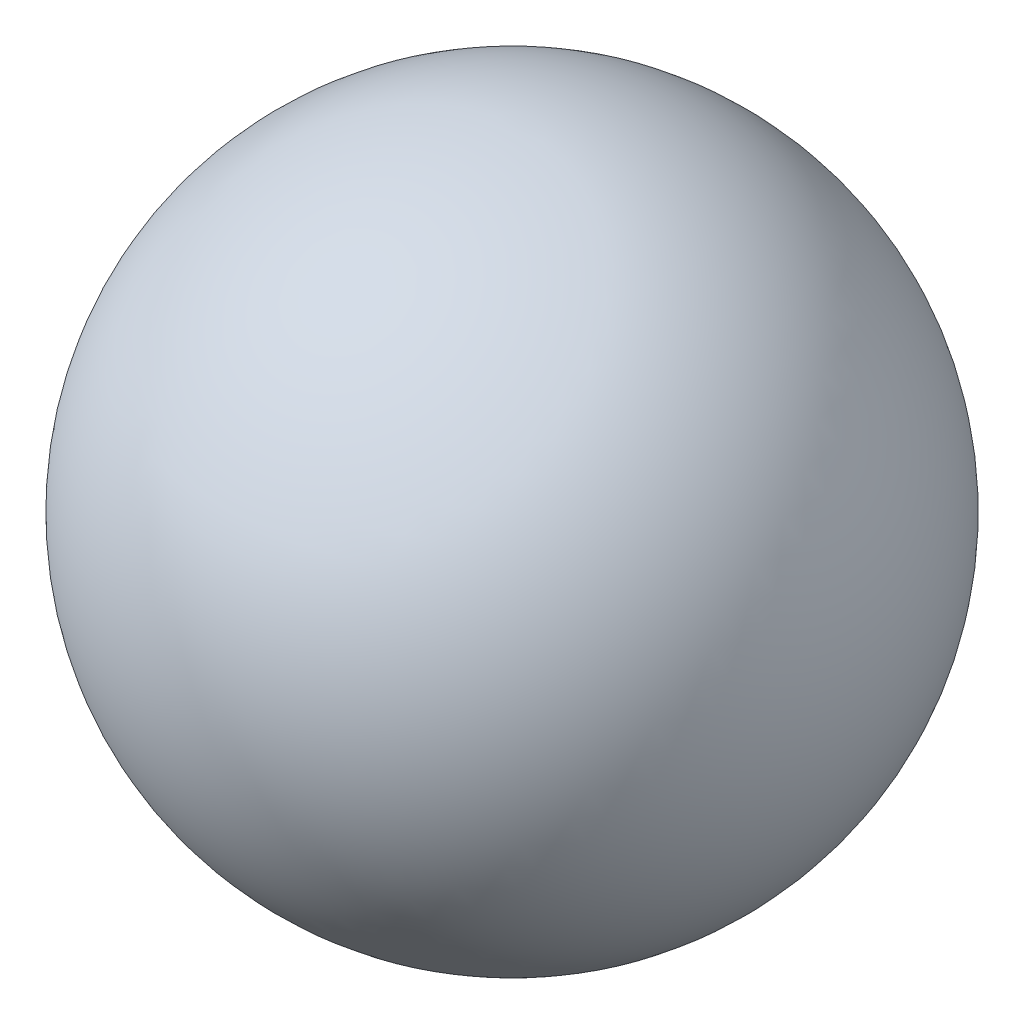
SolidWorks part; units mm, degrees
material "Cast Carbon Steel"
ref_plane "Front Plane" through (0, 0, 0) normal (0, 0, 1) x (1, 0, 0)
ref_plane "Top Plane" through (0, 0, 0) normal (0, 1, 0) x (1, 0, 0)
ref_plane "Right Plane" through (0, 0, 0) normal (1, 0, 0) x (0, 0, -1)
sketch "Sketch1" plane through (0, 0, 0) normal (0, 0, 1) x (1, 0, 0)
  line L1 (0, 9.525) -> (0, -9.525)
  arc A0 (0, -9.525) -> (0, 9.525) centre (0, 0) ccw
  dimension "D1" = 19.05
revolve "Revolve4" add sketch "Sketch1" angle 360 about L1
